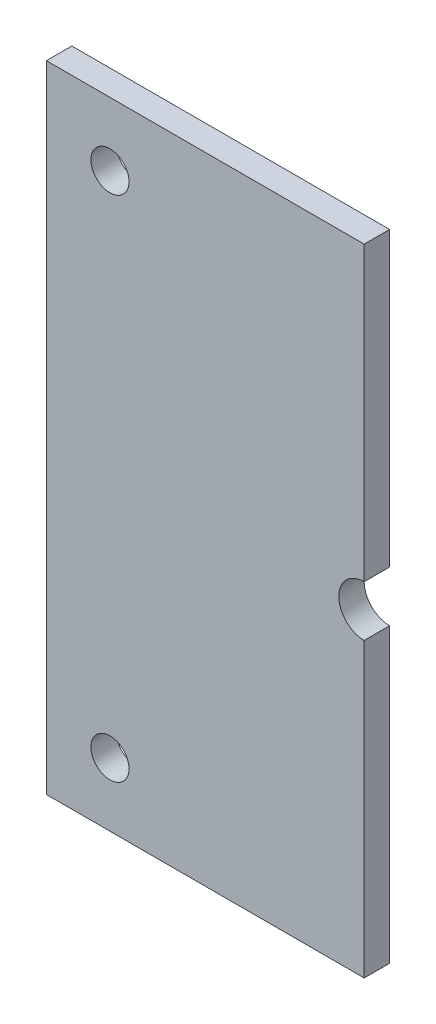
SolidWorks part; units mm, degrees
ref_plane "前视基准面" through (0, 0, 0) normal (0, 0, 1) x (1, 0, 0)
ref_plane "上视基准面" through (0, 0, 0) normal (0, 1, 0) x (1, 0, 0)
ref_plane "右视基准面" through (0, 0, 0) normal (1, 0, 0) x (0, 0, -1)
sketch "草图1" plane through (0, 0, 0) normal (0, 0, 1) x (1, 0, 0)
  line L0 (0, 24.2958) -> (0, -18.2642) construction
  line L1 (-25, 25) -> (25, 25)
  line L2 (-25, 25) -> (-25, -25)
  line L3 (-25, -25) -> (25, -25)
  line L4 (25, 25) -> (25, -25)
  line L5 (-32.2198, 0) -> (32.714, 0) construction
  circle A0 centre (0, 0) radius 2
  circle A1 centre (-20, 20) radius 1.5
  circle A2 centre (20, 20) radius 1.5
  circle A3 centre (20, -20) radius 1.5
  circle A4 centre (-20, -20) radius 1.5
  dimension "D1" = 4
  dimension "D6" = 3
  dimension "D8" = 20
  dimension "D2" = 50
  dimension "D3" = 50
  dimension "D4" = 25
  dimension "D5" = 25
  dimension "D7" = 20
extrude "凸台-拉伸1" add sketch "草图1" along normal blind 2
sketch "草图3" plane through (0, 0, 2) normal (0, 0, 1) x (1, 0, 0)
  line L1 (0, 27.5406) -> (33.6032, 27.5406)
  line L2 (0, 27.5406) -> (0, -27.641)
  line L3 (0, -27.641) -> (33.6032, -27.641)
  line L4 (33.6032, 27.5406) -> (33.6032, -27.641)
extrude "切除-拉伸2" cut sketch "草图3" against normal blind 10
